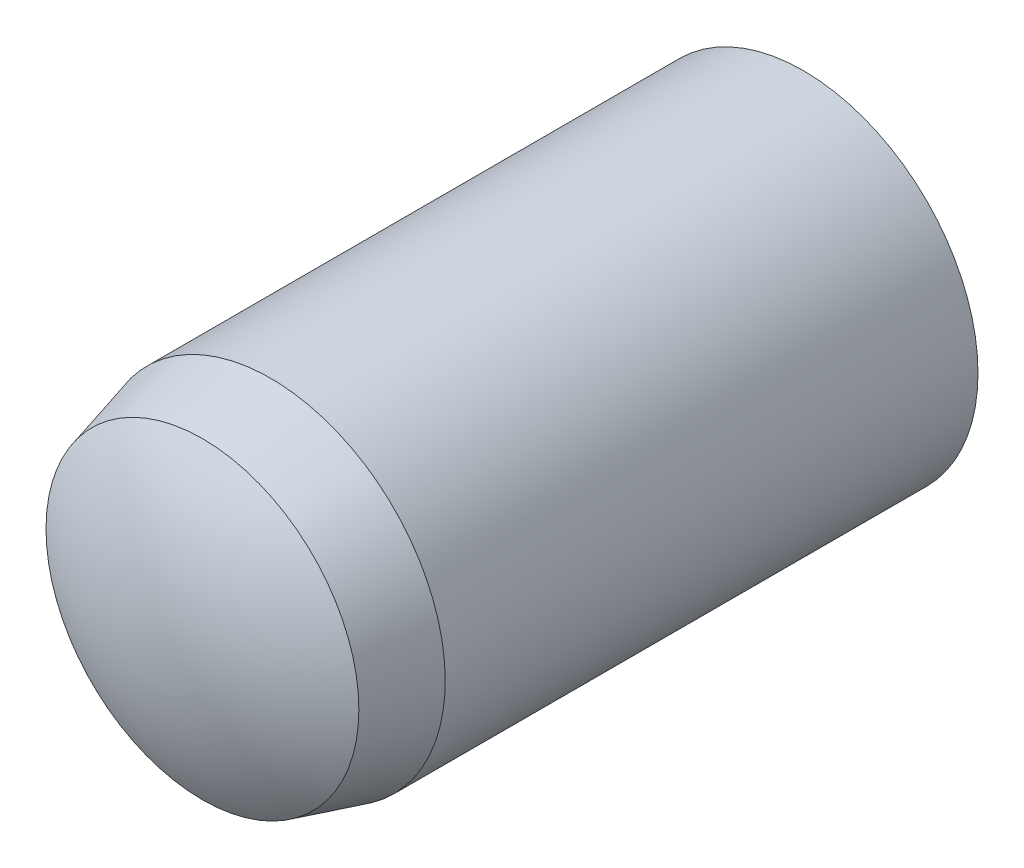
SolidWorks part; units mm, degrees
ref_plane "Front Plane" through (0, 0, 0) normal (0, 0, 1) x (1, 0, 0)
ref_plane "Top Plane" through (0, 0, 0) normal (0, 1, 0) x (1, 0, 0)
ref_plane "Right Plane" through (0, 0, 0) normal (1, 0, 0) x (0, 0, -1)
sketch "Sketch1" plane through (0, 0, 0) normal (0, 0, 1) x (1, 0, 0)
  circle A0 centre (0, 0) radius 4
  point P3 (0, 4)
  dimension "Diameter" = 8
sketch "Sketch2" plane through (0, 0, 0) normal (1, 0, 0) x (0, 0, -1)
  line L0 (-8, 0) -> (8, 0) construction
  line L1 (-8, 0) -> (-8, 4) construction
  line L2 (-8, 4) -> (8, 4)
  line L3 (8, 4) -> (8, 0) construction
  line L4 (-6.96, 3.582) -> (-5.4, 4)
  arc A0 (-8, 0) -> (-6.96, 3.582) centre (-1.3114, 0) cw
  arc A1 (8, 0) -> (6.8, 4) centre (0.7333, 0) ccw
  point P2 (0, 0)
  dimension "Length" = 16
  dimension "D1" = 15
  dimension "D2" = 1.2
  dimension "D3" = 2.6
  dimension "D4" = 1.56
sketch "Sketch3" plane through (0, 0, 0) normal (1, 0, 0) x (0, 0, -1)
  line L0 (-8, 0) -> (8, 0) construction
  line L1 (-6.96, 3.582) -> (-5.4, 4) construction
  line L2 (-8, 0) -> (8, 0)
  line L3 (-6.96, 3.582) -> (-5.4, 4)
  line L4 (-5.4, 4) -> (6.8, 4)
  arc A0 (8, 0) -> (6.8, 4) centre (0.7333, 0) ccw construction
  arc A1 (-6.96, 3.582) -> (-8, 0) centre (-1.3114, 0) ccw construction
  arc A2 (8, 0) -> (6.8, 4) centre (0.7333, 0) ccw
  arc A3 (-6.96, 3.582) -> (-8, 0) centre (-1.3114, 0) ccw
revolve "Revolve1" add sketch "Sketch3" angle 360 about L2
equation "\"D2@Sketch2\" = \"Diameter@Sketch1\" * .15"
equation "\"D3@Sketch2\" = \"Diameter@Sketch1\" * .325"
equation "\"D4@Sketch2\" = \"D3@Sketch2\" * .6"
